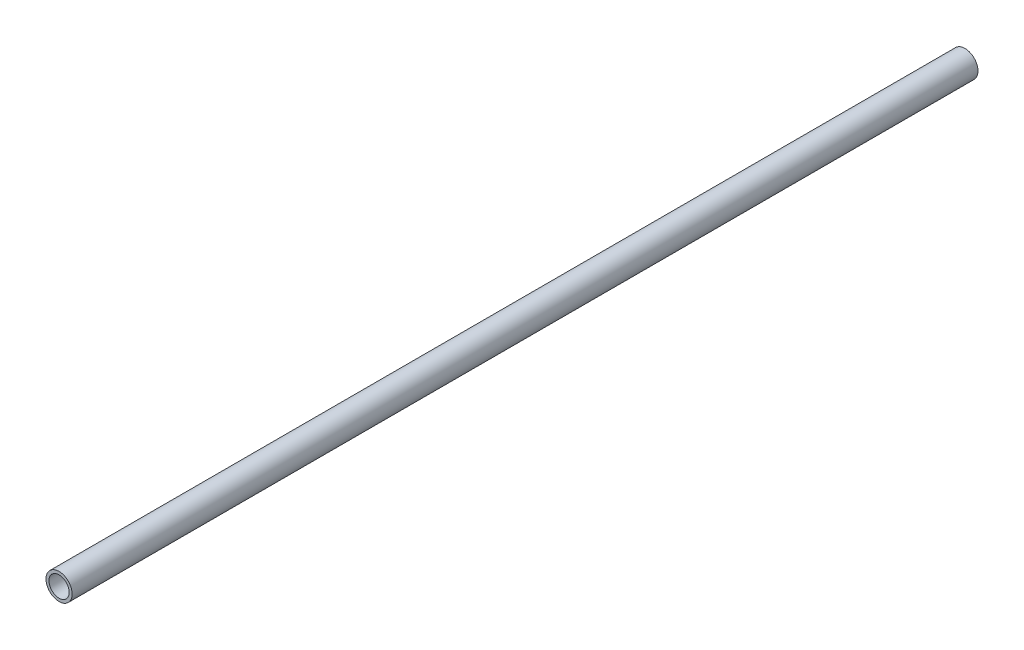
SolidWorks part; units mm, degrees
material "Hexcel AS4C (3000 Filaments)"
ref_plane "Front Plane" through (0, 0, 0) normal (0, 0, 1) x (1, 0, 0)
ref_plane "Top Plane" through (0, 0, 0) normal (0, 1, 0) x (1, 0, 0)
ref_plane "Right Plane" through (0, 0, 0) normal (1, 0, 0) x (0, 0, -1)
sketch "Sketch1" plane through (0, 0, 0) normal (0, 0, 1) x (1, 0, 0)
  circle A0 centre (0, 0) radius 4.7625
  circle A1 centre (0, 0) radius 3.683
  dimension "D1" = 7.366
  dimension "D2" = 9.525
extrude "Boss-Extrude1" add sketch "Sketch1" along normal mid plane 330.2
